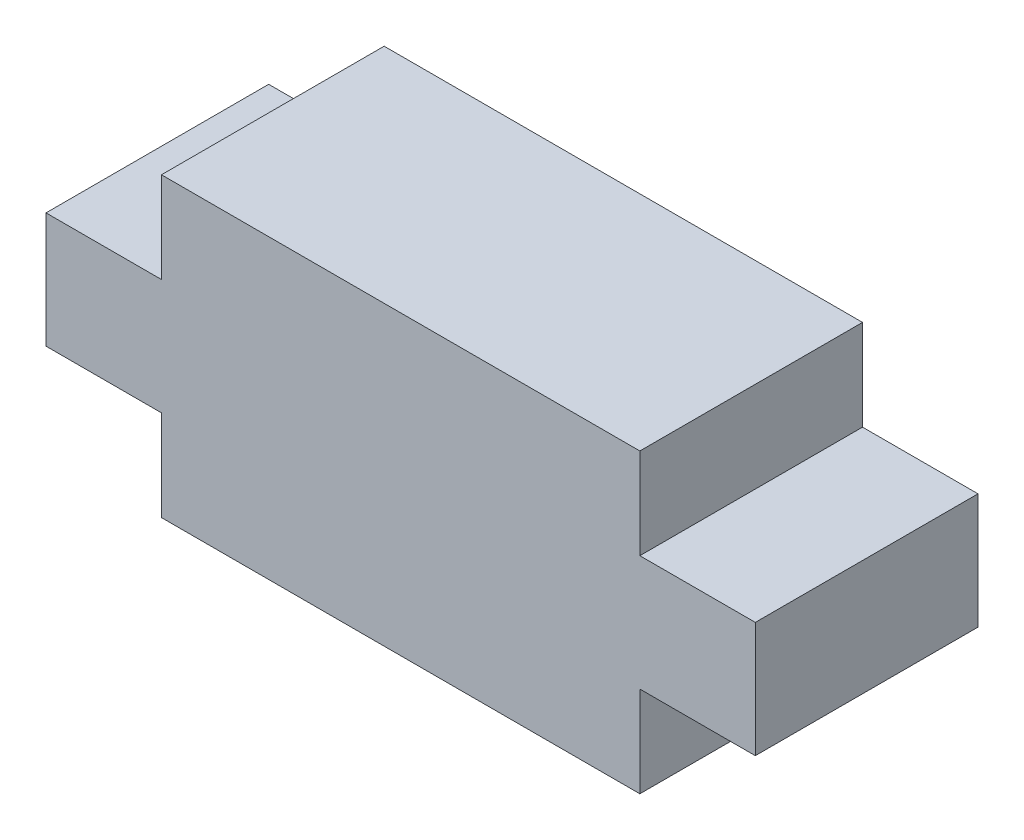
SolidWorks part; units mm, degrees
ref_plane "前视基准面" through (0, 0, 0) normal (0, 0, 1) x (1, 0, 0)
ref_plane "上视基准面" through (0, 0, 0) normal (0, 1, 0) x (1, 0, 0)
ref_plane "右视基准面" through (0, 0, 0) normal (1, 0, 0) x (0, 0, -1)
sketch "草图1" plane through (0, 0, 0) normal (0, 0, 1) x (1, 0, 0)
  line L0 (2.15, 0.35) -> (1.45, 0.35)
  line L1 (1.45, 0.35) -> (1.45, 0.9)
  line L2 (1.45, 0.9) -> (-1.45, 0.9)
  line L3 (-1.45, 0.9) -> (-1.45, 0.35)
  line L4 (-1.45, 0.35) -> (-2.15, 0.35)
  line L5 (-2.15, 0.35) -> (-2.15, -0.35)
  line L6 (-2.15, -0.35) -> (-1.45, -0.35)
  line L7 (-1.45, -0.35) -> (-1.45, -0.9)
  line L8 (-1.45, -0.9) -> (1.45, -0.9)
  line L9 (1.45, -0.9) -> (1.45, -0.35)
  line L10 (1.45, -0.35) -> (2.15, -0.35)
  line L11 (2.15, -0.35) -> (2.15, 0.35)
extrude "Component_Outline" add sketch "草图1" along normal blind 1.35 separate body
sketch3d "3D草图1"
  line L0 (0, 0, 0) -> (1, 0, 0)
  line L1 (0, 0, 0) -> (0, 1, 0)
  line L2 (0, 0, 0) -> (0, 0, 1)
  point P0 (0, 0, 0)
